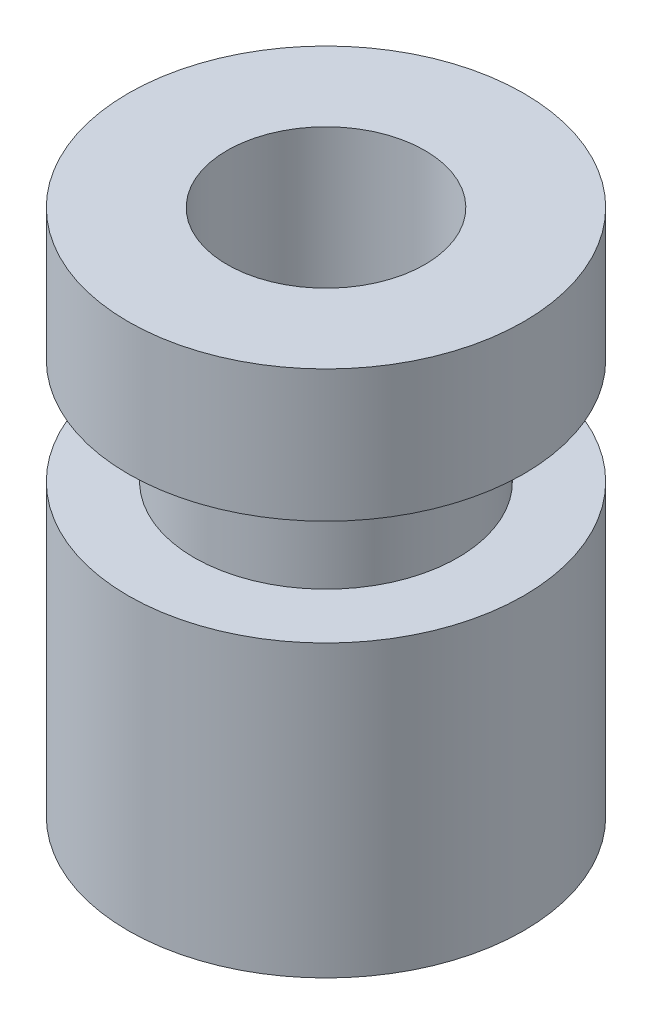
SolidWorks part; units mm, degrees
material "ABS"
ref_plane "Front Plane" through (0, 0, 0) normal (0, 0, 1) x (1, 0, 0)
ref_plane "Top Plane" through (0, 0, 0) normal (0, 1, 0) x (1, 0, 0)
ref_plane "Right Plane" through (0, 0, 0) normal (1, 0, 0) x (0, 0, -1)
sketch "Sketch1" plane through (0, 0, 0) normal (0, 0, 1) x (1, 0, 0)
  line L0 (0, 0) -> (0, 9.1) construction
  line L1 (1.5, 8) -> (3, 8)
  line L2 (3, 8) -> (3, 6)
  line L3 (3, 6) -> (2, 6)
  line L4 (2, 6) -> (2, 4.4)
  line L5 (2, 4.4) -> (3, 4.4)
  line L6 (3, 4.4) -> (3, 0)
  line L7 (3, 0) -> (1.5, 0)
  line L8 (1.5, 8) -> (1.5, 0)
  dimension "D1" = 3
  dimension "D2" = 8
  dimension "D3" = 1.6
  dimension "D4" = 2
  dimension "D5" = 4
  dimension "D6" = 3
revolve "Revolve1" add sketch "Sketch1" angle 360 about L0
